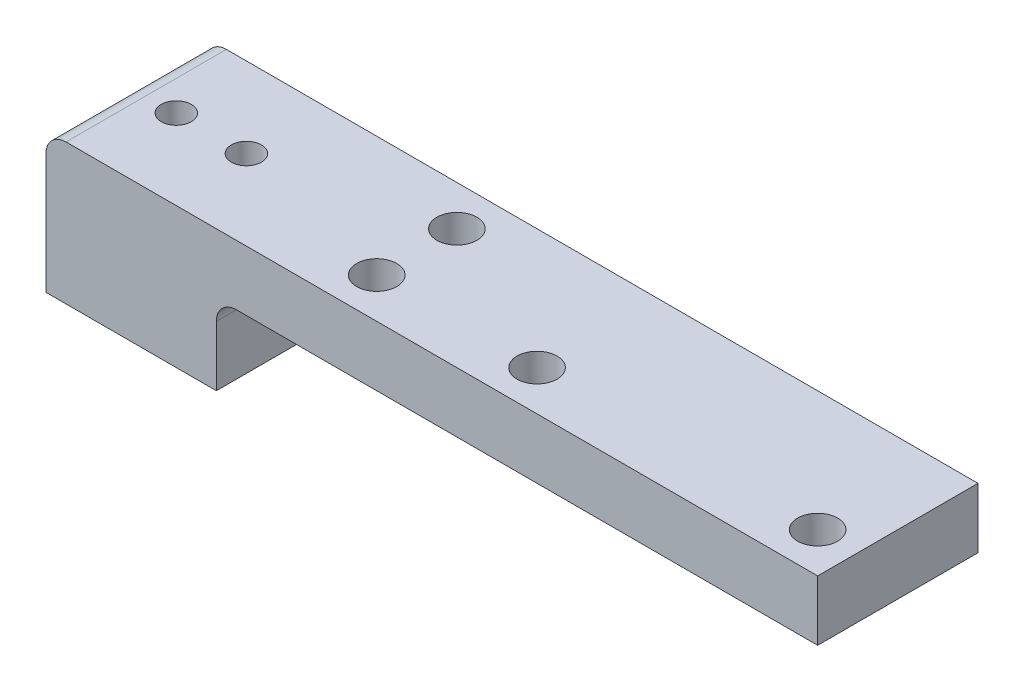
SolidWorks part; units mm, degrees
material "Stainless Steel (ferritic)"
ref_plane "Front Plane" through (0, 0, 0) normal (0, 0, 1) x (1, 0, 0)
ref_plane "Top Plane" through (0, 0, 0) normal (0, 1, 0) x (1, 0, 0)
ref_plane "Right Plane" through (0, 0, 0) normal (1, 0, 0) x (0, 0, -1)
sketch "Sketch1" plane through (0, 0, 0) normal (0, 1, 0) x (1, 0, 0)
  line L0 (-8.5, 0) -> (8.5, 0) construction
  line L1 (-8.5, 8) -> (8.5, 8)
  line L2 (-8.5, 8) -> (-8.5, -8)
  line L3 (-8.5, -8) -> (8.5, -8)
  line L4 (8.5, 8) -> (8.5, -8)
  line L5 (-8.5, 8) -> (8.5, -8) construction
  line L6 (-8.5, -8) -> (8.5, 8) construction
  circle A0 centre (-3.5, 0) radius 1.5
  circle A1 centre (3.5, 0) radius 1.5
  point P0 (0, 0)
  dimension "D3" = 3
  dimension "D4" = 3
  dimension "D1" = 17
  dimension "D2" = 16
  dimension "D5" = 7
  dimension "D6" = 5
extrude "Boss-Extrude1" add sketch "Sketch1" along normal blind 14
sketch "Sketch3" plane through (8.5, 0, 0) normal (1, 0, 0) x (0, 0, -1)
  line L1 (-8, 14) -> (8, 14)
  line L2 (-8, 14) -> (-8, 8)
  line L3 (-8, 8) -> (8, 8)
  line L4 (8, 14) -> (8, 8)
  dimension "D1" = 6
extrude "Boss-Extrude2" add sketch "Sketch3" along normal blind 60
sketch "Sketch4" plane through (0, 14, 0) normal (0, 1, 0) x (1, 0, 0)
  line L0 (36.5, -4) -> (64.5, -4) construction
  line L1 (64.5, -4) -> (68.5, -4) construction
  line L2 (68.5, 8) -> (68.5, -8) construction
  line L3 (32.5, 8) -> (32.5, -8) construction
  line L4 (68.5, 8) -> (-8.5, 8) construction
  line L5 (-8.5, -8) -> (68.5, -8) construction
  line L6 (32.5, -4) -> (36.5, -4) construction
  line L7 (36.5, 8) -> (36.5, -8) construction
  line L8 (64.5, 8) -> (64.5, -8) construction
  line L9 (20.5, 8) -> (20.5, 4) construction
  line L10 (20.5, 4) -> (20.5, -4) construction
  line L11 (20.5, -4) -> (20.5, -8) construction
  line L12 (8.5, 8) -> (8.5, -8) construction
  line L13 (20.5, 4) -> (8.5, 4) construction
  line L14 (20.5, 4) -> (32.5, 4) construction
  circle A0 centre (36.5, -4) radius 2
  circle A1 centre (64.5, -4) radius 2
  circle A2 centre (20.5, 4) radius 2
  circle A3 centre (20.5, -4) radius 2
  circle A4 centre (20.5, 4) radius 3.75 construction
  circle A5 centre (20.5, -4) radius 3.75 construction
  dimension "D1" = 4
  dimension "D2" = 4
  dimension "D6" = 4
  dimension "D7" = 4
  dimension "D8" = 7.5
  dimension "D3" = 28
  dimension "D4" = 36
  dimension "D5" = 4
  dimension "D9" = 17
  dimension "D10" = 8
extrude "Cut-Extrude1" cut sketch "Sketch4" against normal through all
fillet "Fillet1" radius 2 1 edges at (8.5, 8, 0)
fillet "Fillet2" radius 2 1 edges at (-8.5, 14, 0)
